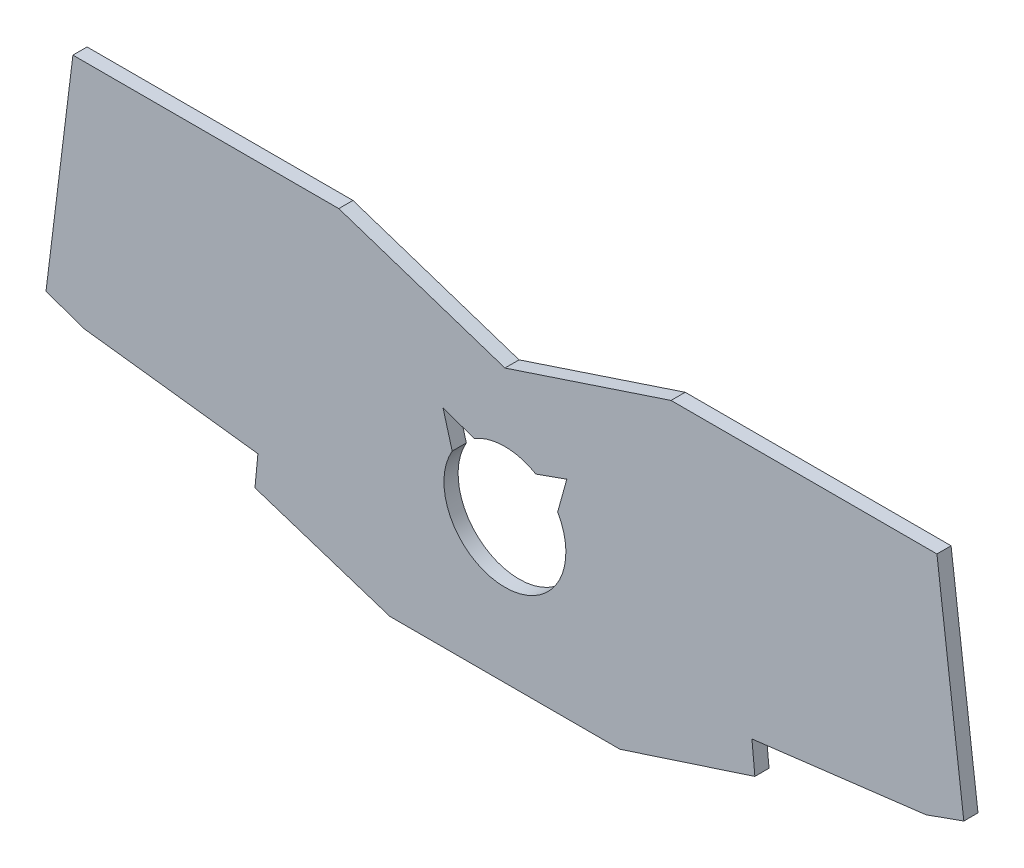
SolidWorks part; units mm, degrees
ref_plane "Спереди" through (0, 0, 0) normal (0, 0, 1) x (1, 0, 0)
ref_plane "Сверху" through (0, 0, 0) normal (0, 1, 0) x (1, 0, 0)
ref_plane "Справа" through (0, 0, 0) normal (1, 0, 0) x (0, 0, -1)
sketch "Эскиз1" plane through (0, 0, 0) normal (0, 0, 1) x (1, 0, 0)
  line L0 (148.6587, -23.6716) -> (87.19, -31.2162)
  line L1 (162, -18.92) -> (148.6587, -23.6716)
  line L2 (-152.5, 58) -> (-58.64, 58)
  line L3 (87.19, -31.2162) -> (88.2371, -42.1562)
  line L4 (-10.9082, 11.6263) -> (-21.8482, 15.5133)
  line L5 (152.5, 58) -> (162, -18.92)
  line L6 (-88.2371, -42.1562) -> (-40.5971, -57.6623)
  line L7 (-58.64, 58) -> (0, 38.59)
  line L8 (-152.5, 58) -> (-162, -18.92)
  line L9 (58.64, 58) -> (0, 38.59)
  line L10 (-87.19, -31.2162) -> (-88.2371, -42.1562)
  line L11 (-40.5971, -57.6623) -> (40.5971, -57.6623)
  line L12 (-162, -18.92) -> (-148.6587, -23.6716)
  line L13 (0, 58) -> (0, -106.1018) construction
  line L14 (-148.6587, -23.6716) -> (-87.19, -31.2162)
  line L15 (88.2371, -42.1562) -> (40.5971, -57.6623)
  line L16 (152.5, 58) -> (58.64, 58)
  line L17 (-21.8482, 15.5133) -> (-18.6176, 3.8733)
  line L18 (21.8482, 15.5133) -> (18.6176, 3.8733)
  line L19 (10.9082, 11.6263) -> (21.8482, 15.5133)
  circle A0 centre (0, -6.93) radius 21.525
  point P0 (0, 0)
  point P19 (0, -57.6623)
  dimension "D1" = 43.05
  dimension "D2" = 10.94
  dimension "D3" = 61.4687
  dimension "D4" = 10.94
  dimension "D5" = 10.99
  dimension "D6" = 47.64
  dimension "D7" = 50.1
  dimension "D8" = 11.64
  dimension "D9" = 12.08
  dimension "D10" = 11.61
  dimension "D11" = 45.52
sketch "Эскиз4" plane through (0, 0, 0) normal (0, 0, 1) x (1, 0, 0)
  line L0 (21.8482, 15.5133) -> (18.6176, 3.8733) construction
  line L1 (10.9082, 11.6263) -> (21.8482, 15.5133) construction
  line L2 (-10.9082, 11.6263) -> (-21.8482, 15.5133) construction
  line L3 (-21.8482, 15.5133) -> (-18.6176, 3.8733) construction
  line L4 (21.8482, 15.5133) -> (18.6176, 3.8733)
  line L5 (10.9082, 11.6263) -> (21.8482, 15.5133)
  line L6 (-10.9082, 11.6263) -> (-21.8482, 15.5133)
  line L7 (-21.8482, 15.5133) -> (-18.6176, 3.8733)
  line L15 (152.5, 58) -> (58.64, 58)
  line L16 (58.64, 58) -> (0, 38.59)
  line L17 (0, 38.59) -> (-58.64, 58)
  line L18 (-58.64, 58) -> (-152.5, 58)
  line L19 (-152.5, 58) -> (-162, -18.92)
  line L20 (-162, -18.92) -> (-148.6587, -23.6716)
  line L21 (-148.6587, -23.6716) -> (-87.19, -31.2162)
  line L22 (-87.19, -31.2162) -> (-88.2371, -42.1562)
  line L23 (-88.2371, -42.1562) -> (-40.5971, -57.6623)
  line L24 (-40.5971, -57.6623) -> (40.5971, -57.6623)
  line L25 (40.5971, -57.6623) -> (88.2371, -42.1562)
  line L26 (88.2371, -42.1562) -> (87.19, -31.2162)
  line L27 (87.19, -31.2162) -> (148.6587, -23.6716)
  line L28 (148.6587, -23.6716) -> (162, -18.92)
  line L29 (162, -18.92) -> (152.5, 58)
  line L30 (152.5, 58) -> (58.64, 58)
  line L31 (58.64, 58) -> (0, 38.59)
  line L32 (0, 38.59) -> (-58.64, 58)
  line L33 (-58.64, 58) -> (-152.5, 58)
  line L34 (-152.5, 58) -> (-162, -18.92)
  line L35 (-162, -18.92) -> (-148.6587, -23.6716)
  line L36 (-148.6587, -23.6716) -> (-87.19, -31.2162)
  line L37 (-87.19, -31.2162) -> (-88.2371, -42.1562)
  line L38 (-88.2371, -42.1562) -> (-40.5971, -57.6623)
  line L39 (-40.5971, -57.6623) -> (40.5971, -57.6623)
  line L40 (40.5971, -57.6623) -> (88.2371, -42.1562)
  line L41 (88.2371, -42.1562) -> (87.19, -31.2162)
  line L42 (87.19, -31.2162) -> (148.6587, -23.6716)
  line L43 (148.6587, -23.6716) -> (162, -18.92)
  line L44 (162, -18.92) -> (152.5, 58)
  circle A1 centre (0, -6.93) radius 21.525
  circle A2 centre (0, -6.93) radius 21.525
  dimension "D1" = 0
  dimension "D2" = 0
extrude "Бобышка-Вытянуть2" add sketch "Эскиз4" along normal blind 5 contours L43 L44 L30 L31 L32 L33 L34 L35 L36 L37 L38 L39 L40 L41 L42 A2 L5 L4 L7 L6
sketch "Эскиз5" plane through (0, 0, 5) normal (0, 0, 1) x (1, 0, 0)
sketch "Эскиз6" plane through (0, 0, 5) normal (0, 0, 1) x (1, 0, 0)
  line L0 (152.5, 58) -> (58.64, 58) construction
  line L1 (147.5014, -18.7761) -> (81.7489, -26.8465) construction
  line L2 (156.5464, -15.5547) -> (147.5014, -18.7761) construction
  line L3 (-148.0795, 53) -> (-59.446, 53) construction
  line L4 (81.7489, -26.8465) -> (82.878, -38.6423) construction
  line L5 (148.0795, 53) -> (156.5464, -15.5547) construction
  line L6 (-82.878, -38.6423) -> (-39.8039, -52.6623) construction
  line L7 (-59.446, 53) -> (0, 33.3232) construction
  line L8 (-148.0795, 53) -> (-156.5464, -15.5547) construction
  line L9 (59.446, 53) -> (0, 33.3232) construction
  line L10 (-81.7489, -26.8465) -> (-82.878, -38.6423) construction
  line L11 (-39.8039, -52.6623) -> (39.8039, -52.6623) construction
  line L12 (-156.5464, -15.5547) -> (-147.5014, -18.7761) construction
  line L13 (-147.5014, -18.7761) -> (-81.7489, -26.8465) construction
  line L14 (82.878, -38.6423) -> (39.8039, -52.6623) construction
  line L15 (148.0795, 53) -> (59.446, 53) construction
  line L16 (-88.2371, -42.1562) -> (-40.5971, -57.6623) construction
  line L17 (-87.19, -31.2162) -> (-88.2371, -42.1562) construction
  line L18 (-148.6587, -23.6716) -> (-87.19, -31.2162) construction
  line L19 (-162, -18.92) -> (-148.6587, -23.6716) construction
  line L20 (-152.5, 58) -> (-162, -18.92) construction
  line L21 (-152.5, 58) -> (-58.64, 58) construction
  line L22 (152.5, 58) -> (162, -18.92) construction
  line L23 (88.2371, -42.1562) -> (40.5971, -57.6623) construction
  line L24 (87.19, -31.2162) -> (88.2371, -42.1562) construction
  line L25 (148.6587, -23.6716) -> (87.19, -31.2162) construction
  line L27 (162, -18.92) -> (148.6587, -23.6716) construction
  line L28 (-58.64, 58) -> (0, 38.59) construction
  line L30 (58.64, 58) -> (0, 38.59) construction
  point P13 (0, -52.6623)
  dimension "D1" = 0
  dimension "D2" = 5
  dimension "D3" = 5
  dimension "D4" = 5
  dimension "D5" = 5
  dimension "D6" = 5
  dimension "D7" = 5
  dimension "D8" = 5
  dimension "D9" = 5
  dimension "D10" = 5
  dimension "D11" = 5
  dimension "D12" = 5
  dimension "D13" = 5
  dimension "D14" = 5
  dimension "D15" = 5
other "Выровнять группу1"
